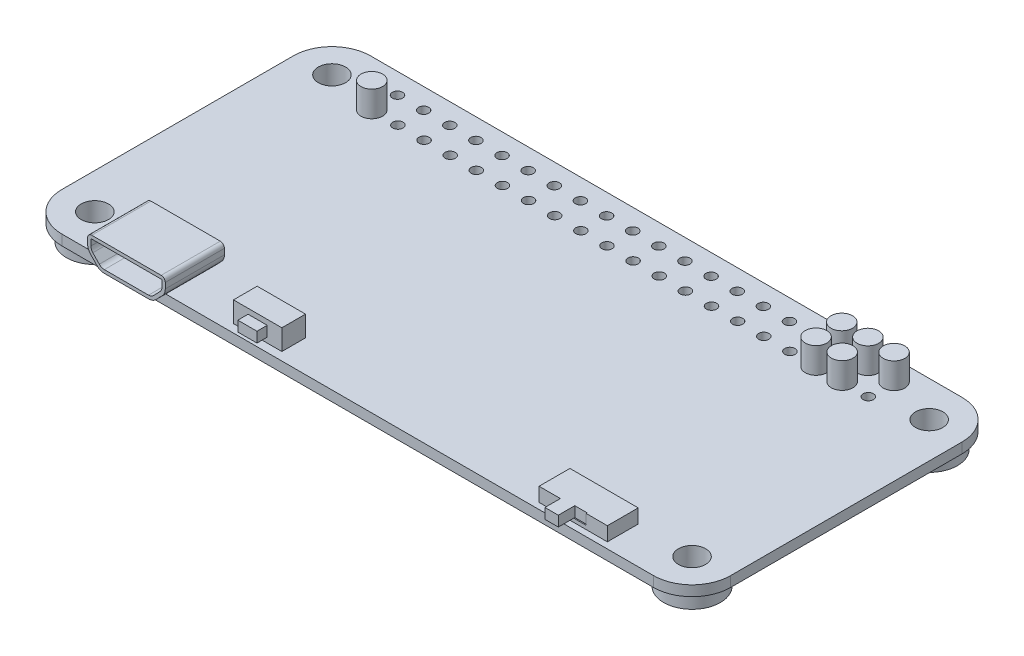
SolidWorks part; units mm, degrees
ref_plane "Front Plane" through (0, 0, 0) normal (0, 0, 1) x (1, 0, 0)
ref_plane "Top Plane" through (0, 0, 0) normal (0, 1, 0) x (1, 0, 0)
ref_plane "Right Plane" through (0, 0, 0) normal (1, 0, 0) x (0, 0, -1)
sketch "Sketch1" plane through (0, 0, 0) normal (0, 1, 0) x (1, 0, 0)
  line L1 (-28.75, 15) -> (28.75, 15)
  line L2 (-32.5, 11.25) -> (-32.5, -11.25)
  line L3 (-28.75, -15) -> (28.75, -15)
  line L4 (32.5, 11.25) -> (32.5, -11.25)
  line L5 (-32.5, 15) -> (32.5, -15) construction
  line L6 (-32.5, -15) -> (32.5, 15) construction
  arc A0 (-32.5, -11.25) -> (-28.75, -15) centre (-28.75, -11.25) ccw
  arc A1 (28.75, -15) -> (32.5, -11.25) centre (28.75, -11.25) ccw
  arc A2 (28.75, 15) -> (32.5, 11.25) centre (28.75, 11.25) cw
  arc A3 (-28.75, 15) -> (-32.5, 11.25) centre (-28.75, 11.25) ccw
  point P0 (0, 0)
  dimension "D3" = 3.75
  dimension "D1" = 65
  dimension "D2" = 30
extrude "Boss-Extrude1" add sketch "Sketch1" along normal blind 1 contours L1 A2 L4 A1 L3 A0 L2 A3
sketch "Sketch2" plane through (0, 1, 0) normal (0, 1, 0) x (1, 0, 0)
  line L0 (0, 15) -> (0, -15) construction
  line L1 (-28.75, 15) -> (28.75, 15) construction
  line L2 (-28.75, -15) -> (28.75, -15) construction
  line L3 (-32.5, 0) -> (32.5, 0) construction
  line L4 (-32.5, 11.25) -> (-32.5, -11.25) construction
  line L5 (32.5, 11.25) -> (32.5, -11.25) construction
  circle A0 centre (-29.025, 11.525) radius 1.325
  circle A2 centre (29.025, 11.525) radius 1.325
  circle A3 centre (29.025, -11.525) radius 1.325
  circle A4 centre (-29.025, -11.525) radius 1.325
  dimension "D1" = 2.65
  dimension "D2" = 2.15
  dimension "D3" = 2.15
extrude "Cut-Extrude1" cut sketch "Sketch2" against normal through all
sketch "Sketch3" plane through (0, 1, 0) normal (0, 1, 0) x (1, 0, 0)
  line L0 (-24.128, 13) -> (-24.128, 10.5) construction
  line L3 (-28.75, 15) -> (28.75, 15) construction
  line L5 (-32.5, 11.25) -> (-32.5, -11.25) construction
  circle A0 centre (-24.128, 13) radius 0.5
  circle A1 centre (-24.128, 10.5) radius 0.5
  dimension "D1" = 1
  dimension "D3" = 1.5
  dimension "D4" = 7.872
  dimension "D2" = 2.5
extrude "Cut-Extrude2" cut sketch "Sketch3" against normal through all
pattern_linear "LPattern1" count 20 spacing 2.54 along (1, 0, 0) of "Cut-Extrude2"
sketch "Sketch15" plane through (0, 0, 15) normal (0, 0, 1) x (1, 0, 0)
  line L0 (-21.225, 1) -> (-21.225, 3.6) construction
  line L1 (-28.75, 1) -> (28.75, 1) construction
  line L2 (-24.6, 3.6) -> (-17.85, 3.6)
  line L3 (-17.45, 3.2) -> (-17.45, 2.6523)
  line L4 (-17.7286, 1.9598) -> (-18.3548, 1.3075)
  line L5 (-19.0762, 1) -> (-23.3738, 1)
  line L7 (-24.7214, 1.9598) -> (-24.0952, 1.3075)
  line L8 (-25, 3.2) -> (-25, 2.6523)
  line L9 (15.325, 0) -> (15.325, 5.5788) construction
  line L10 (-28.75, 0) -> (28.75, 0) construction
  line L11 (-32.5, 1) -> (-32.5, 0) construction
  arc A0 (-18.3548, 1.3075) -> (-19.0762, 1) centre (-19.0762, 2) cw
  arc A1 (-24.0952, 1.3075) -> (-23.3738, 1) centre (-23.3738, 2) ccw
  arc A2 (-17.45, 2.6523) -> (-17.7286, 1.9598) centre (-18.45, 2.6523) cw
  arc A3 (-24.7214, 1.9598) -> (-25, 2.6523) centre (-24, 2.6523) cw
  arc A4 (-17.85, 3.6) -> (-17.45, 3.2) centre (-17.85, 3.2) cw
  arc A5 (-25, 3.2) -> (-24.6, 3.6) centre (-24.6, 3.2) cw
  point P14 (-18.65, 1)
  point P17 (-23.8, 1)
  point P20 (-17.45, 2.25)
  point P23 (-25, 2.25)
  point P26 (-17.45, 3.6)
  point P29 (-25, 3.6)
  dimension "D6" = 1
  dimension "D7" = 0.4
  dimension "D1" = 7.55
  dimension "D2" = 2.6
  dimension "D3" = 1.35
  dimension "D4" = 5.15
  dimension "D5" = 7.5
extrude "Boss-Extrude6" add sketch "Sketch15" along normal blind 1.25 and the other way blind 4.5
sketch "Sketch16" plane through (0, 0, 16.25) normal (0, 0, 1) x (1, 0, 0)
  line L30 (-18.5857, 1.5291) -> (-17.9595, 2.1814)
  line L31 (-17.77, 2.6523) -> (-17.77, 3.2)
  line L32 (-17.85, 3.28) -> (-24.6, 3.28)
  line L33 (-24.68, 3.2) -> (-24.68, 2.6523)
  line L34 (-24.4905, 2.1814) -> (-23.8643, 1.5291)
  line L35 (-23.3738, 1.32) -> (-19.0762, 1.32)
  line L36 (-18.5857, 1.5291) -> (-17.9595, 2.1814)
  line L37 (-17.77, 2.6523) -> (-17.77, 3.2)
  line L38 (-17.85, 3.28) -> (-24.6, 3.28)
  line L39 (-24.68, 3.2) -> (-24.68, 2.6523)
  line L40 (-24.4905, 2.1814) -> (-23.8643, 1.5291)
  line L41 (-23.3738, 1.32) -> (-19.0762, 1.32)
  arc A30 (-19.0762, 1.32) -> (-18.5857, 1.5291) centre (-19.0762, 2) ccw
  arc A31 (-17.9595, 2.1814) -> (-17.77, 2.6523) centre (-18.45, 2.6523) ccw
  arc A32 (-17.77, 3.2) -> (-17.85, 3.28) centre (-17.85, 3.2) ccw
  arc A33 (-24.6, 3.28) -> (-24.68, 3.2) centre (-24.6, 3.2) ccw
  arc A34 (-24.68, 2.6523) -> (-24.4905, 2.1814) centre (-24, 2.6523) ccw
  arc A35 (-23.8643, 1.5291) -> (-23.3738, 1.32) centre (-23.3738, 2) ccw
  arc A36 (-19.0762, 1.32) -> (-18.5857, 1.5291) centre (-19.0762, 2) ccw
  arc A37 (-17.9595, 2.1814) -> (-17.77, 2.6523) centre (-18.45, 2.6523) ccw
  arc A38 (-17.77, 3.2) -> (-17.85, 3.28) centre (-17.85, 3.2) ccw
  arc A39 (-24.6, 3.28) -> (-24.68, 3.2) centre (-24.6, 3.2) ccw
  arc A40 (-24.68, 2.6523) -> (-24.4905, 2.1814) centre (-24, 2.6523) ccw
  arc A41 (-23.8643, 1.5291) -> (-23.3738, 1.32) centre (-23.3738, 2) ccw
  dimension "D2" = 0.32
extrude "Cut-Extrude9" cut sketch "Sketch16" against normal blind 5.25
sketch "草图1" plane through (0, 1, 0) normal (0, 1, 0) x (1, 0, 0)
  line L0 (-32.5, 11.25) -> (-32.5, -11.25) construction
  line L1 (-12.87, -11.9) -> (-8.17, -11.9)
  line L2 (-12.87, -11.9) -> (-12.87, -14.2)
  line L3 (-12.87, -14.2) -> (-8.17, -14.2)
  line L4 (-8.17, -11.9) -> (-8.17, -14.2)
  line L5 (-28.75, -15) -> (-23.3738, -15) construction
  dimension "D1" = 4.7
  dimension "D2" = 2.3
  dimension "D3" = 19.63
  dimension "D4" = 0.8
extrude "凸台-拉伸1" add sketch "草图1" along normal blind 2
sketch "草图2" plane through (0, 0, 14.2) normal (0, 0, 1) x (1, 0, 0)
  line L0 (-12.87, 3) -> (-8.17, 3) construction
  line L5 (-11.45, 2.5) -> (-9.59, 2.5)
  line L6 (-11.45, 2.5) -> (-11.45, 1.5)
  line L7 (-11.45, 1.5) -> (-9.59, 1.5)
  line L8 (-9.59, 2.5) -> (-9.59, 1.5)
  line L9 (-11.45, 2.5) -> (-9.59, 1.5) construction
  line L10 (-11.45, 1.5) -> (-9.59, 2.5) construction
  line L11 (-8.17, 3) -> (-8.17, 1) construction
  point P0 (-10.52, 2)
  point P8 (-10.52, 3)
  point P12 (-8.17, 2)
  dimension "D1" = 1.86
  dimension "D2" = 1
extrude "凸台-拉伸2" add sketch "草图2" along normal blind 1
sketch "草图6" plane through (0, 1, 0) normal (0, 1, 0) x (1, 0, 0)
  line L0 (32.5, 11.25) -> (32.5, -11.25) construction
  line L1 (23.67, -11.4) -> (17.03, -11.4)
  line L2 (23.67, -11.4) -> (23.67, -14.4)
  line L3 (23.67, -14.4) -> (17.03, -14.4)
  line L4 (17.03, -11.4) -> (17.03, -14.4)
  line L5 (23.67, -11.4) -> (17.03, -14.4) construction
  line L6 (23.67, -14.4) -> (17.03, -11.4) construction
  line L7 (-19.0762, -15) -> (28.75, -15) construction
  point P0 (20.35, -12.9)
  dimension "D1" = 8.83
  dimension "D2" = 6.64
  dimension "D3" = 3
  dimension "D4" = 0.6
extrude "凸台-拉伸6" add sketch "草图6" along normal blind 1.36
sketch "草图7" plane through (0, 0, 14.4) normal (0, 0, 1) x (1, 0, 0)
  line L0 (17.03, 2.36) -> (23.67, 2.36) construction
  line L1 (19.1, 2.36) -> (21.6, 2.36)
  line L2 (19.1, 2.36) -> (19.1, 1.36)
  line L3 (19.1, 1.36) -> (21.6, 1.36)
  line L4 (21.6, 2.36) -> (21.6, 1.36)
  line L5 (23.67, 2.36) -> (17.03, 2.36) construction
  point P8 (20.35, 2.36)
  point P9 (20.35, 2.36)
  dimension "D1" = 1
  dimension "D2" = 2.5
extrude "切除-拉伸1" cut sketch "草图7" against normal blind 0.1
sketch "草图8" plane through (0, 0, 14.3) normal (0, 0, 1) x (1, 0, 0)
  line L0 (19.1, 2.36) -> (19.1, 1.36) construction
  line L1 (19.1, 2.36) -> (20.4, 2.36)
  line L2 (19.1, 2.36) -> (19.1, 1.36)
  line L3 (19.1, 1.36) -> (20.4, 1.36)
  line L4 (20.4, 2.36) -> (20.4, 1.36)
  line L5 (21.6, 2.36) -> (19.1, 2.36) construction
  line L6 (19.1, 1.36) -> (21.6, 1.36) construction
  dimension "D1" = 1.3
extrude "凸台-拉伸7" add sketch "草图8" along normal blind 1.6
sketch "草图9" plane through (0, 0, 0) normal (0, -1, 0) x (1, 0, 0)
  circle A0 centre (29.025, 11.525) radius 2.75
  circle A1 centre (29.025, -11.525) radius 2.75
  circle A2 centre (-29.025, 11.525) radius 2.75
  circle A3 centre (-29.025, -11.525) radius 2.75
  circle A4 centre (29.025, 11.525) radius 1.325 construction
  circle A5 centre (29.025, -11.525) radius 1.325 construction
  circle A6 centre (-29.025, 11.525) radius 1.325 construction
  circle A7 centre (-29.025, -11.525) radius 1.325 construction
  circle A8 centre (29.025, 11.525) radius 1.325
  circle A9 centre (29.025, -11.525) radius 1.325
  circle A10 centre (-29.025, 11.525) radius 1.325
  circle A11 centre (-29.025, -11.525) radius 1.325
  dimension "D1" = 5.5
extrude "凸台-拉伸8" add sketch "草图9" along normal blind 1.5
sketch "草图10" plane through (0, 1, 0) normal (0, 1, 0) x (1, 0, 0)
  circle A0 centre (24.132, 13) radius 1.05
  circle A1 centre (21.592, 13) radius 1.05
  circle A2 centre (19.052, 13) radius 1.05
  circle A3 centre (21.592, 10.5) radius 1.05
  circle A4 centre (19.052, 10.5) radius 1.05
  circle A5 centre (-24.128, 10.5) radius 1.05
  dimension "D1" = 2.1
extrude "凸台-拉伸9" add sketch "草图10" along normal blind 2.5
sketch "草图11" plane through (0, 1, 0) normal (0, -1, 0) x (1, 0, 0)
  circle A0 centre (24.132, -13) radius 0.5
  circle A1 centre (21.592, -13) radius 0.5
  circle A2 centre (21.592, -10.5) radius 0.5
  circle A3 centre (19.052, -10.5) radius 0.5
  circle A5 centre (19.052, -13) radius 0.5
  circle A7 centre (-24.128, -10.5) radius 0.5
extrude "凸台-拉伸10" add sketch "草图11" along normal blind 3
